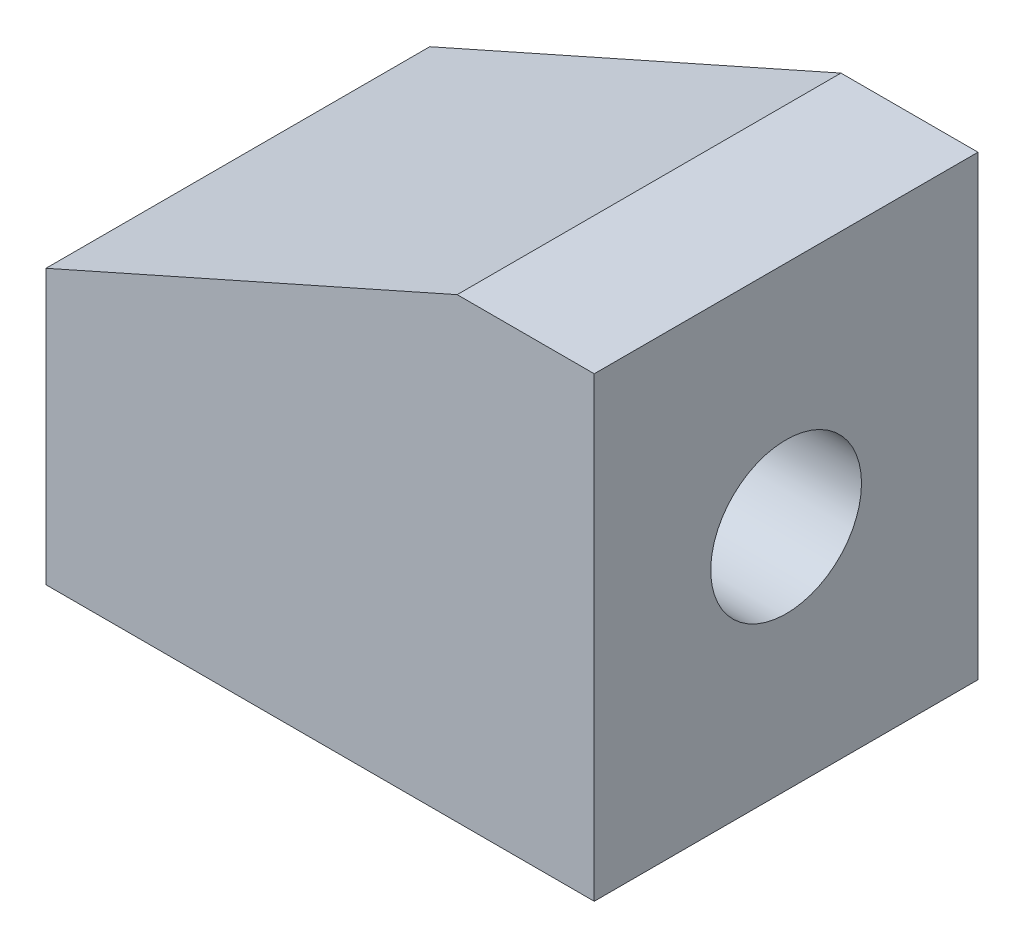
SolidWorks part; units mm, degrees
ref_plane "Piano frontale" through (0, 0, 0) normal (0, 0, 1) x (1, 0, 0)
ref_plane "Piano superiore" through (0, 0, 0) normal (0, 1, 0) x (1, 0, 0)
ref_plane "Piano destro" through (0, 0, 0) normal (1, 0, 0) x (0, 0, -1)
sketch "Schizzo1" plane through (0, 0, 0) normal (0, 0, 1) x (1, 0, 0)
  line L0 (-60, 0) -> (0, 0)
  line L1 (0, 0) -> (0, 50)
  line L2 (0, 50) -> (-15, 50)
  line L3 (-15, 50) -> (-60, 30)
  line L4 (-60, 30) -> (-60, 0)
  point P3 (-66.923, 30)
  point P7 (0, 0)
  dimension "D1" = 30
  dimension "D2" = 60
  dimension "D3" = 50
  dimension "D4" = 15
extrude "Estrusione-Estrusione1" add sketch "Schizzo1" along normal blind 42
sketch "Schizzo2" plane through (0, 0, 0) normal (1, 0, 0) x (0, 0, -1)
  line L0 (-21, 50) -> (-21, 0) construction
  line L1 (-42, 50) -> (0, 50) construction
  line L2 (-42, 0) -> (0, 0) construction
  circle A0 centre (-21, 25) radius 9
  dimension "D1" = 18
  dimension "D2" = 25
hole_wizard "Foro filettato M18x1.5-1" positions "Schizzo3D1" profile "Schizzo3" tap size "M18x1.5" standard "ISO"
sketch3d "Schizzo3D1"
  point P0 (0, 25, 21)
sketch "Schizzo3" plane through (0, 25, 21) normal (0, 1, 0) x (0, 0, -1)
  line L0 (0, 0) -> (0, 48.4571)
  line L1 (0, 48.4571) -> (8.25, 43.5)
  line L2 (8.25, 43.5) -> (8.25, 0)
  line L5 (8.25, 0) -> (0, 0)
  line L10 (0, 48.4571) -> (-8.25, 43.5) construction
  line L11 (0, -6.35) -> (0, 107.95) construction
  dimension "Tap Drill Dia." = 16.5
  dimension "Tap Drill Depth" = 43.5
  dimension "Drill Angle" = 118
cosmetic thread "Filettatura del foro1" parameters "D1"=36, "D2"=18
